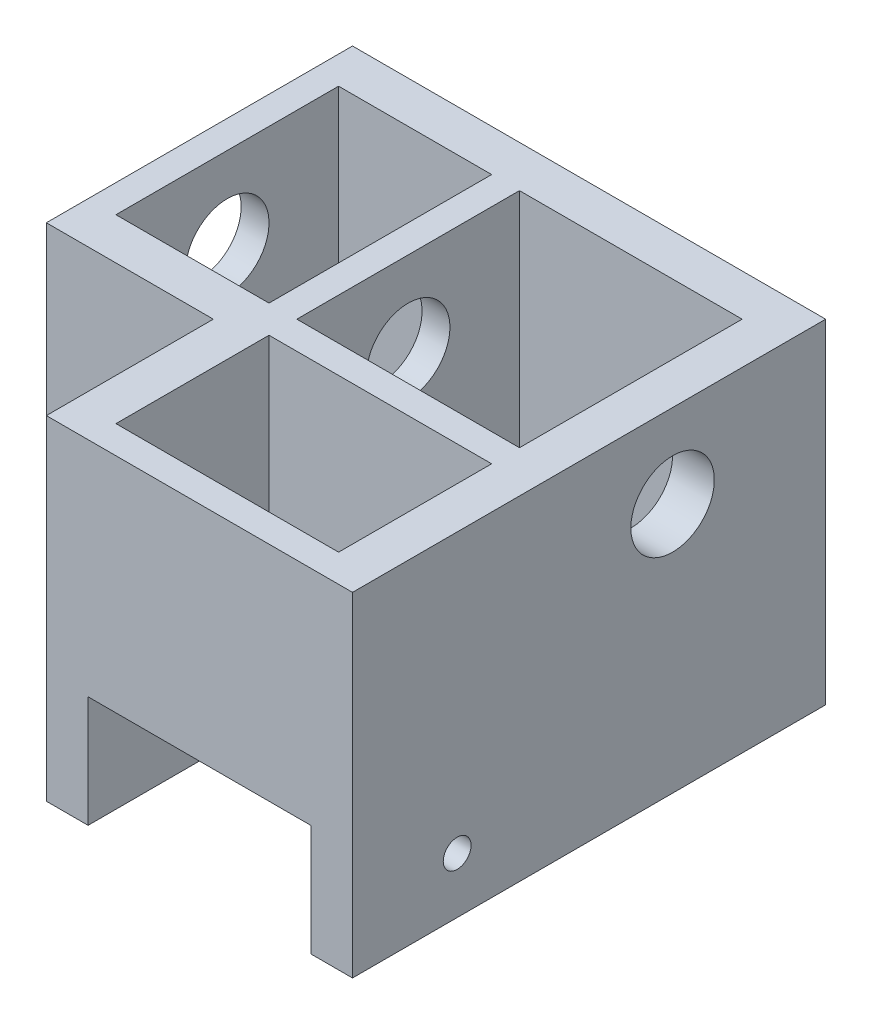
SolidWorks part; units mm, degrees
ref_plane "Front Plane" through (0, 0, 0) normal (0, 0, 1) x (1, 0, 0)
ref_plane "Top Plane" through (0, 0, 0) normal (0, 1, 0) x (1, 0, 0)
ref_plane "Right Plane" through (0, 0, 0) normal (1, 0, 0) x (0, 0, -1)
sketch "Sketch1" plane through (0, 0, 0) normal (0, 1, 0) x (1, 0, 0)
  line L1 (-50.8, -50.8) -> (50.8, -50.8)
  line L2 (-50.8, -50.8) -> (-50.8, 50.8)
  line L3 (-50.8, 50.8) -> (50.8, 50.8)
  line L4 (50.8, -50.8) -> (50.8, 50.8)
  line L5 (-50.8, -50.8) -> (50.8, 50.8) construction
  line L6 (-50.8, 50.8) -> (50.8, -50.8) construction
  point P0 (0, 0)
  dimension "D1" = 101.6
  dimension "D2" = 101.6
extrude "Extrude-Thin1" add sketch "Sketch1" along normal blind 152.4 thin
sketch "Sketch2" plane through (0, 152.4, 0) normal (0, 1, 0) x (1, 0, 0)
  line L0 (-69.85, -69.85) -> (69.85, -69.85) construction
  line L1 (-50.8, -50.8) -> (50.8, -50.8)
  line L2 (-50.8, -50.8) -> (-50.8, -69.85)
  line L3 (-50.8, -69.85) -> (50.8, -69.85)
  line L4 (50.8, -50.8) -> (50.8, -69.85)
ref_plane "Plane1" through (0, 50.8, 0) normal (0, 1, 0) x (1, 0, 0)
sketch "Sketch3" plane through (0, 0, 0) normal (0, -1, 0) x (1, 0, 0)
  line L0 (-69.85, -69.85) -> (-69.85, 69.85) construction
  line L1 (-50.8, 50.8) -> (-69.85, 50.8)
  line L2 (-50.8, 50.8) -> (-50.8, -50.8)
  line L3 (-50.8, -50.8) -> (-69.85, -50.8)
  line L4 (-69.85, 50.8) -> (-69.85, -50.8)
extrude "Cut-Extrude2" cut sketch "Sketch3" against normal up to surface (50.8 mm away)
ref_plane "Plane2" through (72.39, 0, 0) normal (1, 0, 0) x (0, 0, -1)
sketch "Sketch5" plane through (-69.85, 0, 0) normal (-1, 0, 0) x (0, 0, 1)
  line L8 (-50.8, 50.8) -> (50.8, 50.8)
  line L9 (50.8, 50.8) -> (50.8, 0)
  line L10 (50.8, 0) -> (69.85, 0)
  line L11 (69.85, 0) -> (69.85, 152.4)
  line L12 (69.85, 152.4) -> (-69.85, 152.4)
  line L13 (-69.85, 152.4) -> (-69.85, 0)
  line L14 (-69.85, 0) -> (-50.8, 0)
  line L15 (-50.8, 0) -> (-50.8, 50.8)
  line L16 (-50.8, 50.8) -> (50.8, 50.8)
  line L17 (50.8, 50.8) -> (50.8, 0)
  line L18 (50.8, 0) -> (69.85, 0)
  line L19 (69.85, 0) -> (69.85, 152.4)
  line L20 (69.85, 152.4) -> (-69.85, 152.4)
  line L21 (-69.85, 152.4) -> (-69.85, 0)
  line L22 (-69.85, 0) -> (-50.8, 0)
  line L23 (-50.8, 0) -> (-50.8, 50.8)
  dimension "D1" = 0
extrude "Boss-Extrude2" add sketch "Sketch5" along normal blind 76.2
ref_plane "Plane3" through (0, 0, 0) normal (-0.7071, 0, -0.7071) x (-0.7071, 0, 0.7071)
sketch "Sketch6" plane through (0, 152.4, 0) normal (0, 1, 0) x (1, 0, 0)
  line L0 (-50.8, 50.8) -> (-50.8, -50.8) construction
  line L1 (-133.35, 50.8) -> (-63.5, 50.8)
  line L2 (-133.35, 50.8) -> (-133.35, -50.8)
  line L3 (-133.35, -50.8) -> (-63.5, -50.8)
  line L4 (-63.5, 50.8) -> (-63.5, -50.8)
  line L5 (-146.05, -69.85) -> (-146.05, 69.85) construction
  line L6 (50.8, 50.8) -> (-50.8, 50.8) construction
  line L7 (-50.8, -50.8) -> (50.8, -50.8) construction
  dimension "D1" = 12.7
  dimension "D2" = 12.7
extrude "Cut-Extrude3" cut sketch "Sketch6" against normal through all
sketch "Sketch8" plane through (0, 0, 69.85) normal (0, 0, 1) x (1, 0, 0)
  line L0 (-146.05, 0) -> (-146.05, 50.8) construction
  line L1 (-146.05, 0) -> (-146.05, 152.4) construction
  line L2 (-146.05, 25.4) -> (-98.298, 25.4) construction
  circle A0 centre (-98.298, 25.4) radius 6.35
  dimension "D3" = 12.7
  dimension "D1" = 50.8
  dimension "D2" = 47.752
extrude "Cut-Extrude4" cut sketch "Sketch8" against normal through all
mirror "Mirror3" about plane through (0, 0, 0) normal (-0.7071, 0, -0.7071) of "Cut-Extrude3", "Boss-Extrude2", "Cut-Extrude2", "Cut-Extrude4"
mirror "Mirror5" about plane through (72.39, 0, 0) normal (1, 0, 0) of bodies 111
sketch "Sketch9" plane through (72.39, 0, 0) normal (1, 0, 0) x (0, 0, -1)
  line L1 (-146.05, 152.4) -> (69.85, 152.4)
  line L2 (-146.05, 152.4) -> (-146.05, 0)
  line L3 (-146.05, 0) -> (69.85, 0)
  line L4 (69.85, 152.4) -> (69.85, 0)
extrude "Cut-Extrude6" cut sketch "Sketch9" along normal through all
sketch "Sketch10" plane through (-146.05, 0, 0) normal (-1, 0, 0) x (0, 0, 1)
  line L0 (0, 152.4) -> (0, 114.3)
  line L1 (69.85, 152.4) -> (-69.85, 152.4) construction
  circle A0 centre (0, 114.3) radius 19.05
  dimension "D2" = 38.1
  dimension "D1" = 38.1
extrude "Cut-Extrude7" cut sketch "Sketch10" against normal through all both
